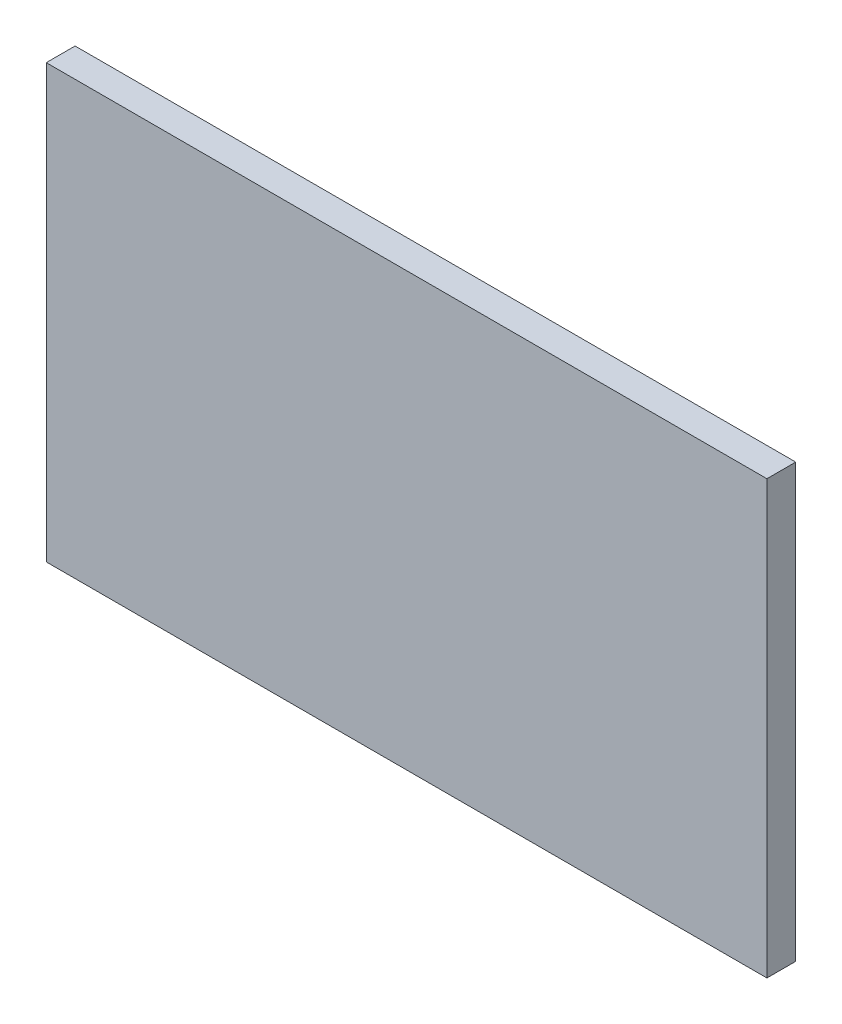
SolidWorks part; units mm, degrees
ref_plane "Front Plane" through (0, 0, 0) normal (0, 0, 1) x (1, 0, 0)
ref_plane "Top Plane" through (0, 0, 0) normal (0, 1, 0) x (1, 0, 0)
ref_plane "Right Plane" through (0, 0, 0) normal (1, 0, 0) x (0, 0, -1)
sketch "Sketch1" plane through (0, 0, 0) normal (0, 0, 1) x (1, 0, 0)
  line L1 (0, 0) -> (-100, 0)
  line L2 (0, 0) -> (0, -60)
  line L3 (0, -60) -> (-100, -60)
  line L4 (-100, 0) -> (-100, -60)
  dimension "D1" = 100
  dimension "D2" = 60
extrude "Boss-Extrude1" add sketch "Sketch1" along normal blind 4
